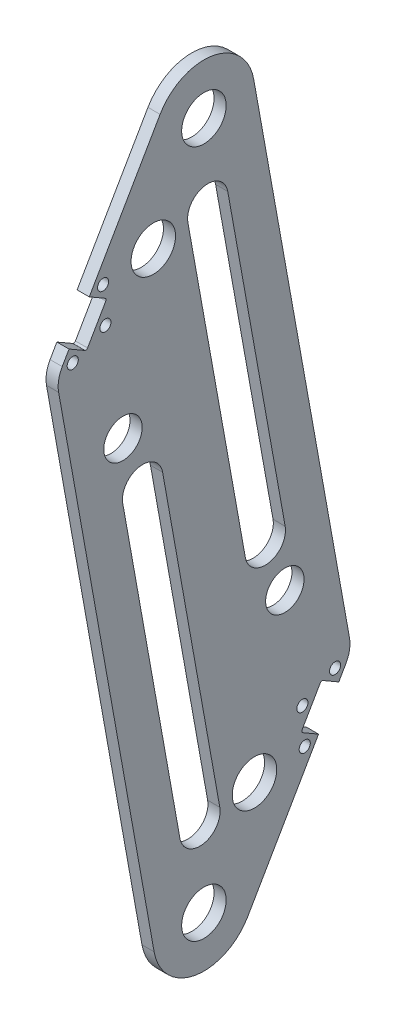
SolidWorks part; units mm, degrees
ref_plane "前视基准面" through (0, 0, 0) normal (0, 0, 1) x (1, 0, 0)
ref_plane "上视基准面" through (0, 0, 0) normal (0, 1, 0) x (1, 0, 0)
ref_plane "右视基准面" through (0, 0, 0) normal (1, 0, 0) x (0, 0, -1)
other "Configuration Table"
sketch "草图1" plane through (0, 0, 0) normal (1, 0, 0) x (0, 0, -1)
  line L0 (0, 0) -> (40, -222)
  line L1 (40, -222) -> (-25, -43.3013)
  line L2 (-25, -43.3013) -> (0, 0)
  line L3 (0, 0) -> (0, -340) construction
  line L4 (0, -340) -> (25, -296.6987)
  line L5 (25, -296.6987) -> (-40, -117)
  line L6 (-40, -117) -> (0, -340)
  line L8 (0, -340) -> (-40, -340)
  line L11 (-40, -340) -> (-40, -117)
  circle A0 centre (0, 0) radius 11
  circle A1 centre (-25, -43.3013) radius 11
  circle A2 centre (25, -296.6987) radius 11
  circle A3 centre (0, -340) radius 11
  circle A4 centre (40, -222) radius 9.5
  circle A5 centre (-40, -117) radius 9.5
  circle A6 centre (-25, -43.3013) radius 14
  circle A7 centre (-40, -117) radius 11.5
  dimension "D7" = 22
  dimension "D8" = 19
  dimension "D9" = 28
  dimension "D10" = 23
  dimension "D1" = 50
  dimension "D2" = 40
  dimension "D3" = 222
  dimension "D4" = 40
  dimension "D5" = 340
  dimension "D6" = 223
  dimension "D11" = 30
  dimension "D12" = 30
sketch "草图2" plane through (0, 0, 0) normal (1, 0, 0) x (0, 0, -1)
  line L0 (12.4943, 71.6408) -> (-72.7516, -76.0094)
  line L1 (-25, -43.3013) -> (0, 0) construction
  line L2 (-72.7516, -76.0094) -> (-12.5358, -411.7126)
  line L3 (-12.5358, -411.7126) -> (72.9169, -263.7043)
  line L4 (72.9169, -263.7043) -> (12.4943, 71.6408)
  line L5 (-40, -117) -> (0, -340) construction
  line L6 (0, 0) -> (40, -222) construction
  line L7 (0, -340) -> (25, -296.6987) construction
  circle A0 centre (-40, -117) radius 9.5 construction
  circle A1 centre (25, -296.6987) radius 11 construction
  circle A2 centre (0, -340) radius 11 construction
  circle A3 centre (-25, -43.3013) radius 11 construction
  circle A4 centre (40, -222) radius 9.5 construction
  circle A5 centre (0, 0) radius 11 construction
  circle A6 centre (-40, -117) radius 9.5
  circle A7 centre (25, -296.6987) radius 11
  circle A8 centre (0, -340) radius 11
  circle A9 centre (-25, -43.3013) radius 11
  circle A10 centre (40, -222) radius 9.5
  circle A11 centre (0, 0) radius 11
  dimension "D1" = 25
  dimension "D2" = 25
  dimension "D3" = 25
  dimension "D4" = 25
extrude "凸台-拉伸1" add sketch "草图2" along normal blind 6
sketch "草图3" plane through (6, 0, 0) normal (1, 0, 0) x (0, 0, -1)
  line L1 (12.4943, 71.6408) -> (-72.7516, -76.0094) construction
  line L3 (-72.7516, -76.0094) -> (-12.5358, -411.7126) construction
  line L5 (72.9169, -263.7043) -> (12.4943, 71.6408) construction
  line L8 (-12.5358, -411.7126) -> (72.9169, -263.7043) construction
  line L12 (-30.2487, -143.0438) -> (-2, -300.5304) construction
  line L13 (-20.4058, -141.2783) -> (7.843, -298.7648)
  line L14 (-40.0916, -144.8094) -> (-11.8429, -302.2959)
  line L15 (-40, -117) -> (0, -340) construction
  line L16 (-16.1243, -221.7871) -> (-20, -228.5) construction
  line L17 (0, 0) -> (40, -222) construction
  line L18 (1.9419, -38.9745) -> (30.3139, -196.4389) construction
  line L19 (11.7834, -37.2012) -> (40.1554, -194.6656)
  line L20 (-7.8996, -40.7477) -> (20.4724, -198.2121)
  line L21 (16.1279, -117.7067) -> (20, -111) construction
  arc A4 (-20.4058, -141.2783) -> (-40.0916, -144.8094) centre (-30.2487, -143.0438) ccw
  arc A5 (-11.8429, -302.2959) -> (7.843, -298.7648) centre (-2, -300.5304) ccw
  arc A6 (11.7834, -37.2012) -> (-7.8996, -40.7477) centre (1.9419, -38.9745) ccw
  arc A7 (20.4724, -198.2121) -> (40.1554, -194.6656) centre (30.3139, -196.4389) ccw
  point P30 (-16.1243, -221.7871)
  point P47 (16.1279, -117.7067)
  dimension "D7" = 10
  dimension "D9" = 10
  dimension "D5" = 160
  dimension "D6" = 30
  dimension "D8" = 160
  dimension "D10" = 30
extrude "切除-拉伸1" cut sketch "草图3" against normal blind 10
fillet "圆角1" radius 25 2 edges at (3, -411.7126, 12.5358) (3, 71.6408, -12.4943)
sketch "草图4" plane through (6, 0, 0) normal (1, 0, 0) x (0, 0, -1)
  line L0 (-66.6506, -65.4423) -> (-56.6506, -48.1218)
  line L1 (-66.6506, -65.4423) -> (-57.9904, -70.4423)
  line L2 (-56.6506, -48.1218) -> (-47.9904, -53.1218)
  line L3 (-57.9904, -70.4423) -> (-47.9904, -53.1218)
  line L4 (-21.6506, 12.5) -> (-72.7516, -76.0094) construction
  line L5 (-61.6506, -56.782) -> (-48.6603, -64.282) construction
  line L6 (-49.8205, -46.2917) -> (-64.8205, -72.2724) construction
  line L7 (-61.6506, -56.782) -> (-52.9904, -61.782) construction
  line L8 (61.6506, -283.218) -> (52.9904, -278.218) construction
  line L9 (21.6506, -352.5) -> (72.9169, -263.7043) construction
  line L10 (64.8205, -267.7276) -> (49.8205, -293.7083) construction
  line L11 (61.6506, -283.218) -> (48.6603, -275.718) construction
  line L12 (47.9904, -286.8782) -> (57.9904, -269.5577)
  line L13 (66.6506, -274.5577) -> (57.9904, -269.5577)
  line L14 (56.6506, -291.8782) -> (47.9904, -286.8782)
  line L15 (56.6506, -291.8782) -> (66.6506, -274.5577)
  line L16 (-61.6506, -56.782) -> (-52.9904, -61.782) construction
  circle A0 centre (-25, -43.3013) radius 20 construction
  circle A1 centre (-49.8205, -46.2917) radius 2.75
  circle A2 centre (-64.8205, -72.2724) radius 2.75
  circle A3 centre (-48.6603, -64.282) radius 2.75
  circle A4 centre (25, -296.6987) radius 20 construction
  circle A5 centre (48.6603, -275.718) radius 2.75
  circle A6 centre (49.8205, -293.7083) radius 2.75
  circle A7 centre (64.8205, -267.7276) radius 2.75
  point P16 (-57.3205, -59.282)
  point P37 (57.3205, -280.718)
  dimension "D3" = 40
  dimension "D6" = 5.5
  dimension "D7" = 20
  dimension "D11" = 5.5
  dimension "D1" = 20
  dimension "D2" = 10
  dimension "D4" = 15
  dimension "D5" = 30
  dimension "D8" = 10
  dimension "D9" = 30
  dimension "D10" = 15
extrude "切除-拉伸2" cut sketch "草图4" against normal blind 10
fillet "圆角2" radius 15 2 edges at (3, -76.0094, 72.7516) (3, -263.7043, -72.9169)
fillet "圆角3" radius 1 4 edges at (3, -70.4423, 57.9904) (3, -53.1218, 47.9904) (3, -286.8782, -47.9904) (3, -269.5577, -57.9904)
sketch "草图5" plane through (6, 0, 0) normal (1, 0, 0) x (0, 0, -1)
  line L0 (0, 0) -> (0, -340) construction
